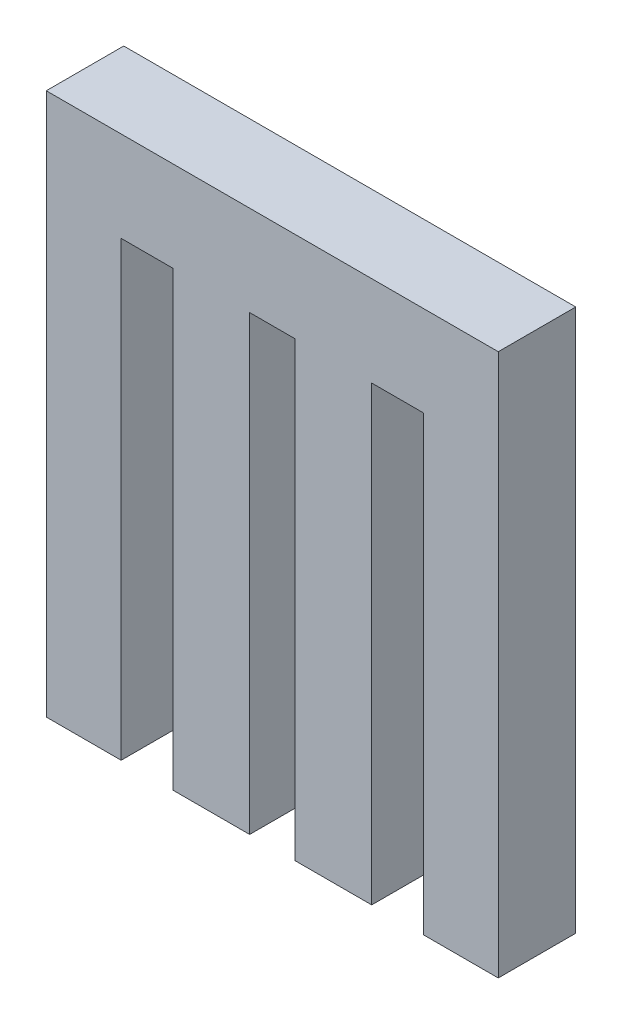
SolidWorks part; units mm, degrees
ref_plane "Plan de face" through (0, 0, 0) normal (0, 0, 1) x (1, 0, 0)
ref_plane "Plan de dessus" through (0, 0, 0) normal (0, 1, 0) x (1, 0, 0)
ref_plane "Plan de droite" through (0, 0, 0) normal (1, 0, 0) x (0, 0, -1)
sketch "Esquisse1" plane through (0, 0, 0) normal (0, 0, 1) x (1, 0, 0)
  line L1 (17.5, -21) -> (-17.5, -21)
  line L2 (17.5, -21) -> (17.5, 21)
  line L3 (17.5, 21) -> (-17.5, 21)
  line L4 (-17.5, -21) -> (-17.5, 21)
  line L5 (17.5, -21) -> (-17.5, 21) construction
  line L6 (17.5, 21) -> (-17.5, -21) construction
  point P0 (0, 0)
  dimension "D1" = 35
  dimension "D2" = 42
extrude "Boss.-Extru.1" add sketch "Esquisse1" along normal blind 6
sketch "Esquisse2" plane through (0, 0, 0) normal (0, 0, -1) x (-1, 0, 0)
  line L0 (17.5, -21) -> (-17.5, -21) construction
  line L1 (-11.7, -21) -> (-7.7, -21)
  line L2 (-11.7, -21) -> (-11.7, 14)
  line L3 (-11.7, 14) -> (-7.7, 14)
  line L4 (-7.7, -21) -> (-7.7, 14)
  line L5 (-17.5, -21) -> (-17.5, 21) construction
  line L6 (17.5, 21) -> (17.5, -21) construction
  line L7 (11.7, -21) -> (7.7, -21)
  line L8 (11.7, -21) -> (11.7, 14)
  line L9 (11.7, 14) -> (7.7, 14)
  line L10 (7.7, -21) -> (7.7, 14)
  line L11 (-1.75, -21) -> (1.75, -21)
  line L12 (-1.75, -21) -> (-1.75, 14)
  line L13 (-1.75, 14) -> (1.75, 14)
  line L14 (1.75, -21) -> (1.75, 14)
  dimension "D1" = 4
  dimension "D2" = 5.8
  dimension "D3" = 5.8
  dimension "D4" = 4
  dimension "D5" = 1.75
  dimension "D7" = 35
  dimension "D8" = 35
  dimension "D9" = 35
  dimension "D10" = 3.5
extrude "Enlèv. mat.-Extru.1" cut sketch "Esquisse2" against normal blind 6
